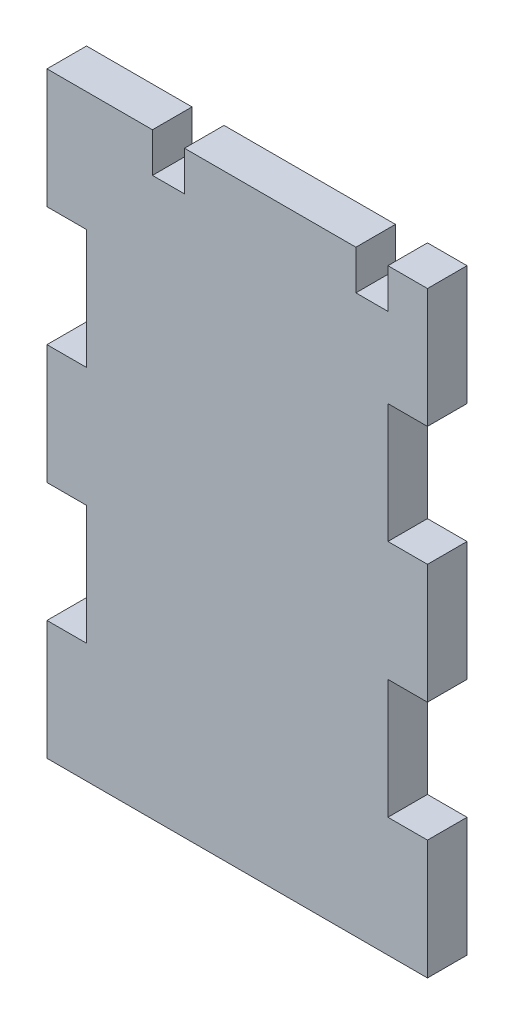
SolidWorks part; units mm, degrees
ref_plane "Front Plane" through (0, 0, 0) normal (0, 0, 1) x (1, 0, 0)
ref_plane "Top Plane" through (0, 0, 0) normal (0, 1, 0) x (1, 0, 0)
ref_plane "Right Plane" through (0, 0, 0) normal (1, 0, 0) x (0, 0, -1)
sketch "Sketch1" plane through (0, 0, 0) normal (0, 0, 1) x (1, 0, 0)
  line L1 (-38.9473, 40.8312) -> (12.3607, 40.8312)
  line L2 (-38.9473, 40.8312) -> (-38.9473, -39.6868)
  line L3 (-38.9473, -39.6868) -> (12.3607, -39.6868)
  line L4 (12.3607, 40.8312) -> (12.3607, -39.6868)
  dimension "D1" = 80.518
  dimension "D2" = 51.308
extrude "Boss-Extrude1" add sketch "Sketch1" along normal blind 5.334
sketch "Sketch2" plane through (0, 0, 5.334) normal (0, 0, 1) x (1, 0, 0)
  line L0 (-38.9473, 40.8312) -> (-38.9473, -39.6868) construction
  line L1 (-38.9473, 24.7276) -> (-33.6133, 24.7276)
  line L2 (-38.9473, 24.7276) -> (-38.9473, 8.624)
  line L3 (-38.9473, 8.624) -> (-33.6133, 8.624)
  line L4 (-33.6133, 24.7276) -> (-33.6133, 8.624)
  line L5 (-33.6133, 24.7276) -> (-33.6133, 40.8312) construction
  line L6 (-38.9473, -7.4796) -> (-33.6133, -7.4796)
  line L7 (-38.9473, -7.4796) -> (-38.9473, -23.5832)
  line L8 (-38.9473, -23.5832) -> (-33.6133, -23.5832)
  line L9 (-33.6133, -7.4796) -> (-33.6133, -23.5832)
  line L10 (12.3607, 40.8312) -> (-38.9473, 40.8312) construction
  line L11 (-33.6133, 8.624) -> (-33.6133, -7.4796) construction
  line L12 (-33.6133, -7.4796) -> (-33.9376, -7.3715) construction
  line L13 (-33.6133, -23.5832) -> (-33.6133, -39.6868) construction
  line L14 (-38.9473, -39.6868) -> (12.3607, -39.6868) construction
  line L15 (-13.2933, 40.8312) -> (-13.2933, -39.6868) construction
  line L16 (7.0267, -23.5832) -> (7.0267, -39.6868) construction
  line L17 (7.0267, -7.4796) -> (7.351, -7.3715) construction
  line L18 (7.0267, 8.624) -> (7.0267, -7.4796) construction
  line L19 (7.0267, 24.7276) -> (7.0267, 40.8312) construction
  line L20 (7.0267, -7.4796) -> (7.0267, -23.5832)
  line L21 (12.3607, -23.5832) -> (7.0267, -23.5832)
  line L22 (12.3607, -7.4796) -> (12.3607, -23.5832)
  line L23 (12.3607, -7.4796) -> (7.0267, -7.4796)
  line L24 (7.0267, 24.7276) -> (7.0267, 8.624)
  line L25 (12.3607, 8.624) -> (7.0267, 8.624)
  line L26 (12.3607, 24.7276) -> (12.3607, 8.624)
  line L27 (12.3607, 24.7276) -> (7.0267, 24.7276)
  dimension "D1" = 5.334
extrude "Cut-Extrude1" cut sketch "Sketch2" against normal through all
sketch "Sketch3" plane through (0, 0, 5.334) normal (0, 0, 1) x (1, 0, 0)
  line L0 (7.0267, 24.7276) -> (7.0267, 40.8312) construction
  line L1 (12.3607, 40.8312) -> (-38.9473, 40.8312) construction
  line L2 (-24.7233, 35.4972) -> (-24.7233, 40.8312)
  line L3 (7.0267, 35.4972) -> (2.7087, 35.4972)
  line L4 (7.0267, 35.4972) -> (7.0267, 40.8312)
  line L5 (7.0267, 40.8312) -> (2.7087, 40.8312)
  line L6 (2.7087, 35.4972) -> (2.7087, 40.8312)
  line L7 (-20.4053, 40.8312) -> (-24.7233, 40.8312)
  line L8 (-20.4053, 35.4972) -> (-20.4053, 40.8312)
  line L9 (-20.4053, 35.4972) -> (-24.7233, 35.4972)
  dimension "D1" = 5.334
  dimension "D4" = 23.114
  dimension "D3" = 2
extrude "Cut-Extrude2" cut sketch "Sketch3" against normal through all
equation "\"MDF\"= .21in"
equation "\"Foamcore\"= .13in"
equation "\"Gmaterial\"= \"MDF\""
equation "\"D2@Sketch1\"=2*\"MDF\"+1.6"
equation "\"D1@Boss-Extrude1\"=\"MDF\""
equation "\"D1@Sketch2\"=\"MDF\""
equation "\"D1@Sketch3\"=\"MDF\""
